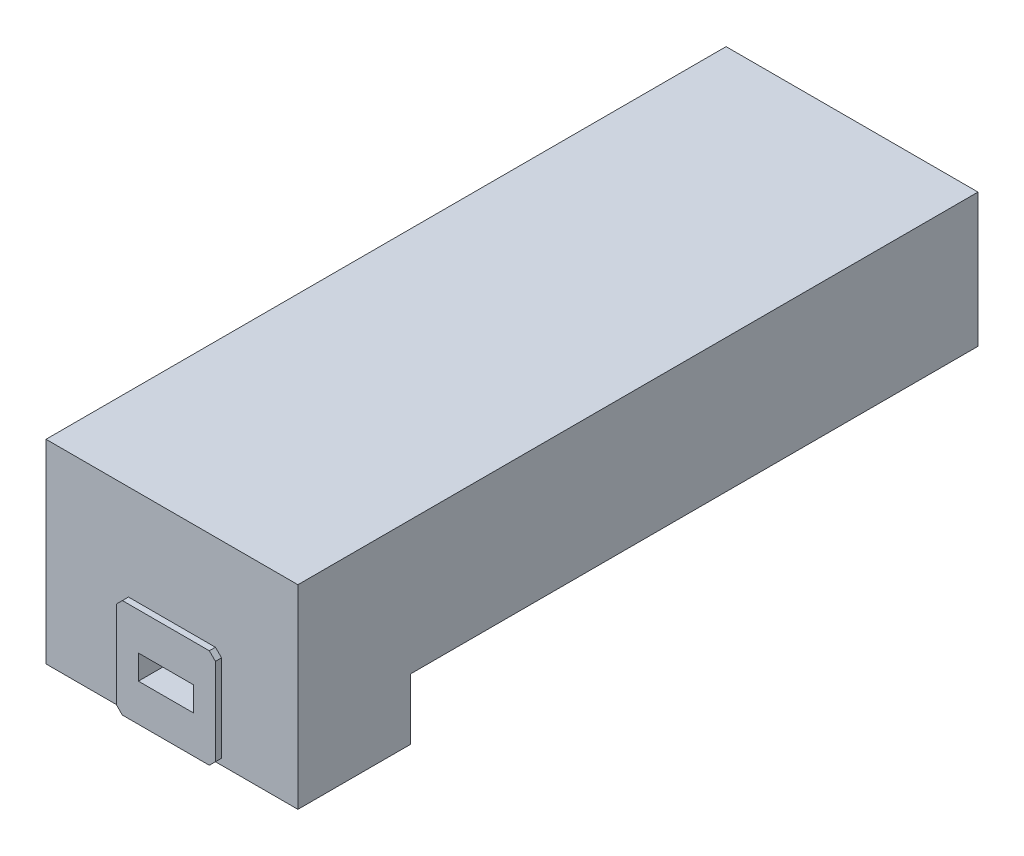
SolidWorks part; units mm, degrees
ref_plane "Front Plane" through (0, 0, 0) normal (0, 0, 1) x (1, 0, 0)
ref_plane "Top Plane" through (0, 0, 0) normal (0, 1, 0) x (1, 0, 0)
ref_plane "Right Plane" through (0, 0, 0) normal (1, 0, 0) x (0, 0, -1)
sketch "Sketch1" plane through (0, 0, 0) normal (1, 0, 0) x (0, 0, -1)
  line L1 (0, 0) -> (111.5, 0)
  line L2 (0, 0) -> (0, 31.9)
  line L3 (0, 31.9) -> (111.5, 31.9)
  line L4 (111.5, 0) -> (111.5, 31.9)
  dimension "D1" = 111.5
  dimension "D2" = 31.9
extrude "Boss-Extrude1" add sketch "Sketch1" against normal blind 41.3
sketch "Sketch2" plane through (0, 0, 0) normal (1, 0, 0) x (0, 0, -1)
  line L0 (0, 0) -> (18.5, 0) construction
  line L1 (0, 0) -> (111.5, 0) construction
  line L2 (18.5, 0) -> (18.5, 10)
  line L3 (18.5, 10) -> (111.5, 10)
  line L4 (111.5, 0) -> (111.5, 31.9) construction
  line L5 (111.5, 10) -> (111.5, 0)
  line L6 (111.5, 0) -> (18.5, 0)
  dimension "D1" = 18.5
  dimension "D2" = 10
extrude "Cut-Extrude1" cut sketch "Sketch2" against normal through all
sketch "Sketch3" plane through (0, 0, 0) normal (0, 0, 1) x (1, 0, 0)
  line L0 (-20.65, 31.9) -> (-20.65, 0) construction
  line L1 (-41.3, 31.9) -> (0, 31.9) construction
  line L2 (-41.3, 0) -> (0, 0) construction
  line L3 (-28.78, 0) -> (-12.52, 0)
  line L4 (-28.78, 0) -> (-28.78, 16.26)
  line L5 (-12.52, 0) -> (-12.52, 16.26)
  line L6 (-28.78, 16.26) -> (-12.52, 16.26)
  point P9 (-20.65, 0)
  dimension "D1" = 16.26
extrude "Boss-Extrude2" add sketch "Sketch3" along normal blind 1
sketch "Sketch4" plane through (0, 0, 1) normal (0, 0, 1) x (1, 0, 0)
  line L0 (-28.78, 8.13) -> (-12.52, 8.13) construction
  line L1 (-28.78, 16.26) -> (-28.78, 0) construction
  line L2 (-12.52, 0) -> (-12.52, 16.26) construction
  line L4 (-25.15, 6.13) -> (-16.15, 6.13)
  line L5 (-25.15, 6.13) -> (-25.15, 10.13)
  line L6 (-25.15, 10.13) -> (-16.15, 10.13)
  line L7 (-16.15, 6.13) -> (-16.15, 10.13)
  line L8 (-25.15, 6.13) -> (-16.15, 10.13) construction
  line L9 (-25.15, 10.13) -> (-16.15, 6.13) construction
  point P6 (-20.65, 8.13)
  point P11 (-16.9066, 5.9611)
  point P12 (-20.65, 8.13)
  dimension "D1" = 9
  dimension "D2" = 4
extrude "Cut-Extrude2" cut sketch "Sketch4" against normal blind 15
chamfer "Chamfer1" distance 1 angle 45 4 edges at (-12.52, 0, 0.5) (-28.78, 0, 0.5) (-28.78, 16.26, 0.5) (-12.52, 16.26, 0.5)
